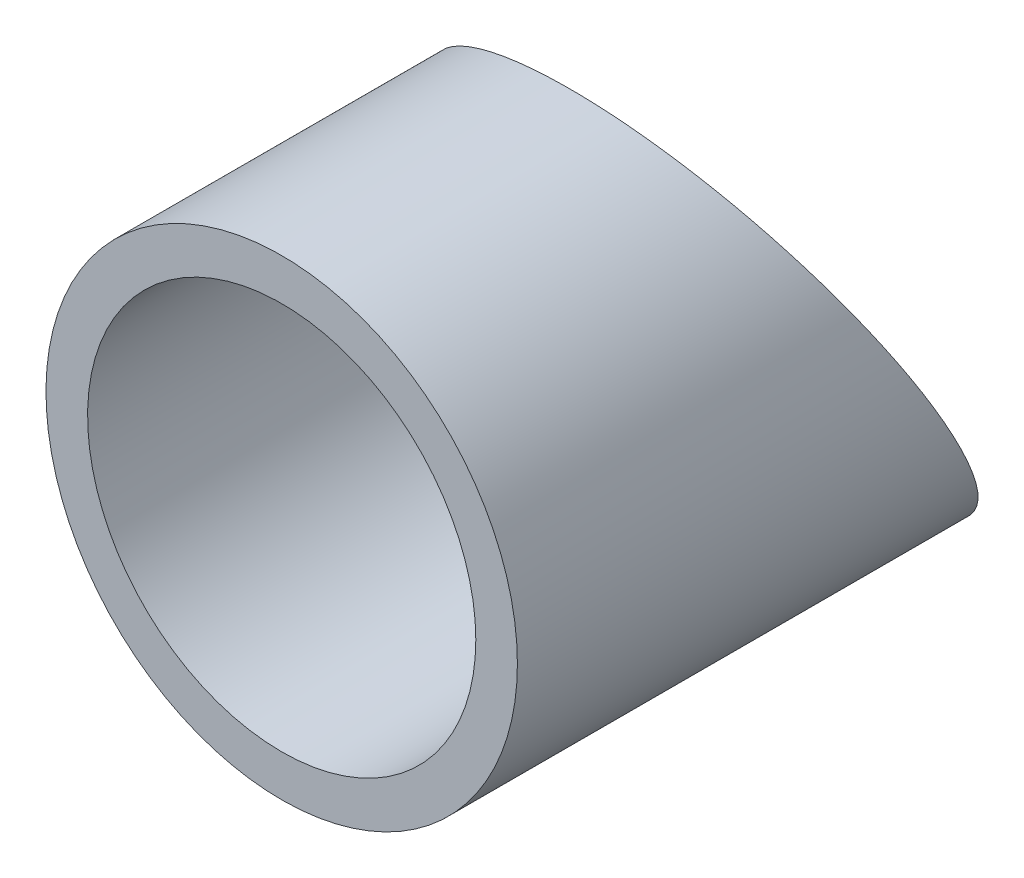
SolidWorks part; units mm, degrees
ref_plane "Front Plane" through (0, 0, 0) normal (0, 0, 1) x (1, 0, 0)
ref_plane "Top Plane" through (0, 0, 0) normal (0, 1, 0) x (1, 0, 0)
ref_plane "Right Plane" through (0, 0, 0) normal (1, 0, 0) x (0, 0, -1)
sketch "Sketch1" plane through (0, 0, 0) normal (0, 0, 1) x (1, 0, 0)
  circle A0 centre (0, 0) radius 17
  circle A1 centre (0, 0) radius 14
  dimension "D1" = 34
  dimension "D2" = 3
extrude "Boss-Extrude1" add sketch "Sketch1" along normal blind 40
sketch "Sketch2" plane through (0, 0, 0) normal (1, 0, 0) x (0, 0, -1)
  line L0 (-34.2292, 43.0612) -> (13.7032, -40.0632)
  line L1 (13.7032, -40.0632) -> (34.2572, -28.2111)
  line L2 (34.2572, -28.2111) -> (-13.6752, 54.9133)
  line L3 (-13.6752, 54.9133) -> (-34.2292, 43.0612)
  ellipse E0 centre (-7.1985, 3.2951) end of major axis (-82.1282, 133.2395) minor radius 3.7489 construction
extrude "Cut-Extrude1" cut sketch "Sketch2" against normal through all and the other way through all
